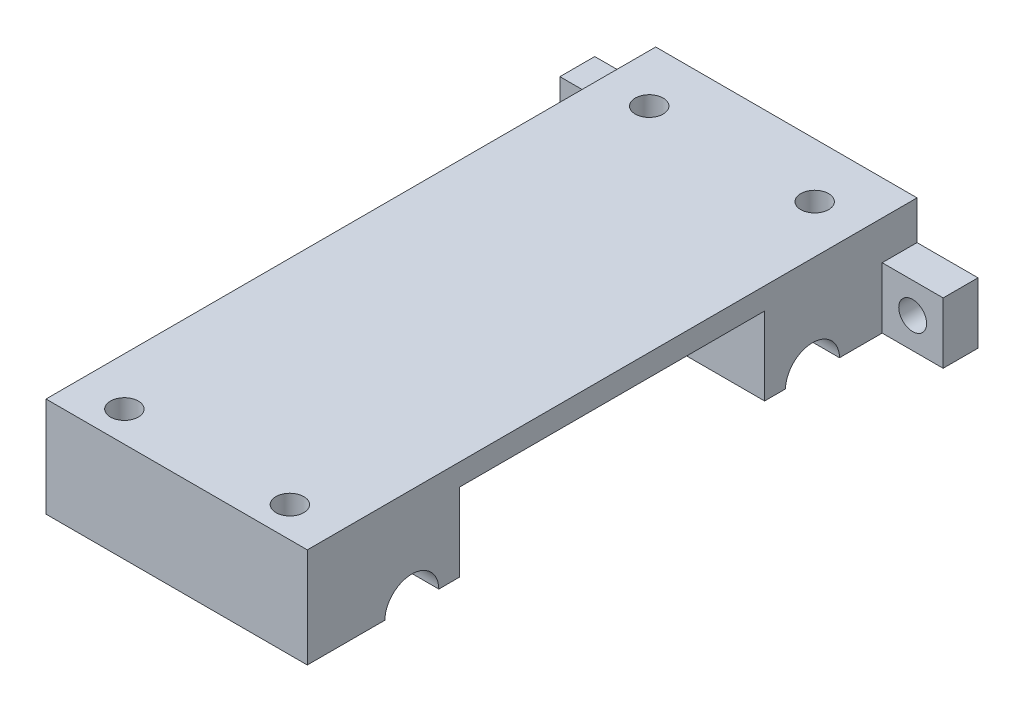
SolidWorks part; units mm, degrees
ref_plane "Front Plane" through (0, 0, 0) normal (0, 0, 1) x (1, 0, 0)
ref_plane "Top Plane" through (0, 0, 0) normal (0, 1, 0) x (1, 0, 0)
ref_plane "Right Plane" through (0, 0, 0) normal (1, 0, 0) x (0, 0, -1)
sketch "Sketch3" plane through (0, 0, 0) normal (0, 1, 0) x (1, 0, 0)
  line L1 (-15, 35) -> (15, 35)
  line L2 (-15, 35) -> (-15, -35)
  line L3 (-15, -35) -> (15, -35)
  line L4 (15, 35) -> (15, -35)
  line L5 (-15, 35) -> (15, -35) construction
  line L6 (-15, -35) -> (15, 35) construction
  point P0 (0, 0)
  dimension "D1" = 70
  dimension "D2" = 30
extrude "Boss-Extrude2" add sketch "Sketch3" along normal blind 10.5 and the other way blind 0.95
sketch "Sketch4" plane through (0, -0.95, 0) normal (0, -1, 0) x (1, 0, 0)
  line L0 (-15, -35) -> (-15, 35) construction
  line L1 (15, -17.5) -> (-15, -17.5)
  line L2 (15, -17.5) -> (15, 17.5)
  line L3 (15, 17.5) -> (-15, 17.5)
  line L4 (-15, -17.5) -> (-15, 17.5)
  line L5 (15, -17.5) -> (-15, 17.5) construction
  line L6 (15, 17.5) -> (-15, -17.5) construction
  point P0 (0, 0)
  dimension "D1" = 35
extrude "Cut-Extrude2" cut sketch "Sketch4" against normal blind 8.95
sketch "Sketch5" plane through (-15, 0, 0) normal (-1, 0, 0) x (0, 0, 1)
  line L0 (17.5, -0.95) -> (35, -0.95) construction
  line L1 (35, 10.5) -> (35, -0.95) construction
  circle A0 centre (-23, -1) radius 3.1
  circle A1 centre (23, -1) radius 3.1
  dimension "D3" = 6.2
  dimension "D4" = 46
  dimension "D1" = 0.05
  dimension "D2" = 12
extrude "Cut-Extrude3" cut sketch "Sketch5" against normal through all
sketch "Sketch6" plane through (0, 10.5, 0) normal (0, 1, 0) x (1, 0, 0)
  line L0 (-15, -35) -> (15, -35) construction
  line L1 (-15, 35) -> (-15, -35) construction
  line L2 (15, -35) -> (15, 35) construction
  line L3 (15, 35) -> (-15, 35) construction
  circle A0 centre (-9.5, 28.75) radius 1.6
  circle A1 centre (9.5, 28.75) radius 1.6
  circle A2 centre (-9.5, -31.5) radius 1.6
  circle A3 centre (9.5, -31.5) radius 1.6
  dimension "D1" = 3.2
  dimension "D2" = 3.2
  dimension "D3" = 3.2
  dimension "D4" = 3.2
  dimension "D5" = 3.5
  dimension "D6" = 3.5
  dimension "D8" = 5.5
  dimension "D9" = 6.25
  dimension "D7" = 5.5
extrude "Cut-Extrude4" cut sketch "Sketch6" against normal through all
sketch "Sketch7" plane through (0, 0, -35) normal (0, 0, -1) x (-1, 0, 0)
  line L2 (-15, -0.95) -> (-22, -0.95)
  line L3 (-15, -0.95) -> (-15, 6.05)
  line L5 (-15, 6.05) -> (-22, 6.05)
  line L6 (-22, -0.95) -> (-22, 6.05)
  line L7 (15, -0.95) -> (22, -0.95)
  line L8 (15, -0.95) -> (15, 6.05)
  line L9 (15, 6.05) -> (22, 6.05)
  line L10 (22, -0.95) -> (22, 6.05)
  circle A0 centre (-18.5, 2.55) radius 1.6
  circle A1 centre (18.5, 2.55) radius 1.5251
  dimension "D1" = 7
  dimension "D5" = 3.2
  dimension "D6" = 3.5
  dimension "D7" = 3.5
  dimension "D8" = 3.5
  dimension "D9" = 3.5
  dimension "D2" = 7
  dimension "D3" = 7
  dimension "D4" = 7
extrude "Boss-Extrude3" add sketch "Sketch7" against normal blind 4
